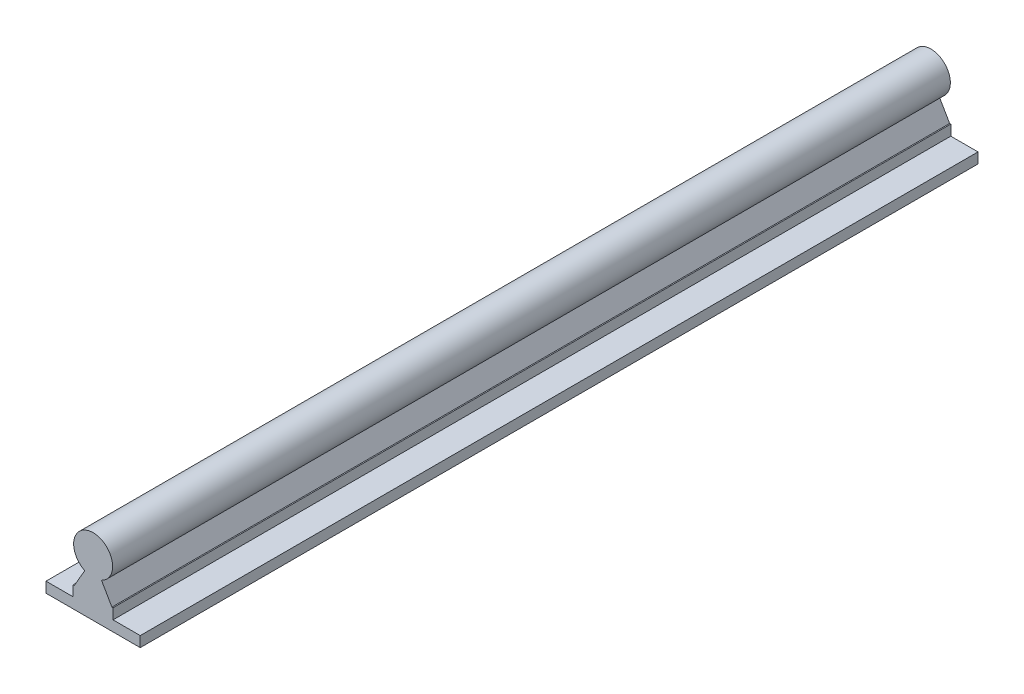
SolidWorks part; units mm, degrees
ref_plane "Front Plane" through (0, 0, 0) normal (0, 0, 1) x (1, 0, 0)
ref_plane "Top Plane" through (0, 0, 0) normal (0, 1, 0) x (1, 0, 0)
ref_plane "Right Plane" through (0, 0, 0) normal (1, 0, 0) x (0, 0, -1)
ref_plane "Plane1"
sketch "Sketch1" plane through (0, 0, 0) normal (0, 0, 1) x (1, 0, 0)
  line L0 (-22.5, 0) -> (22.5, 0)
  line L1 (22.5, 0) -> (22.5, 5)
  line L2 (22.5, 5) -> (9.5, 5)
  line L3 (9.5, 5) -> (9.5, 10)
  line L4 (9.5, 10) -> (8.9676, 10)
  line L5 (8.9676, 10) -> (4, 18.6042)
  line L6 (-4, 18.6042) -> (-8.9676, 10)
  line L7 (-8.9676, 10) -> (-9.5, 10)
  line L8 (-9.5, 10) -> (-9.5, 5)
  line L9 (-9.5, 5) -> (-22.5, 5)
  line L10 (-22.5, 5) -> (-22.5, 0)
  arc A0 (4, 18.6042) -> (-4, 18.6042) centre (0, 27) ccw
  dimension "D8" = 18.6
  dimension "D1" = 45
  dimension "D2" = 5
  dimension "D3" = 5
  dimension "D4" = 19
  dimension "D5" = 13
  dimension "D6" = 10
  dimension "D7" = 5
  dimension "D9" = 8
  dimension "D10" = 270
extrude "Extrusion1" add sketch "Sketch1" along normal blind 400
